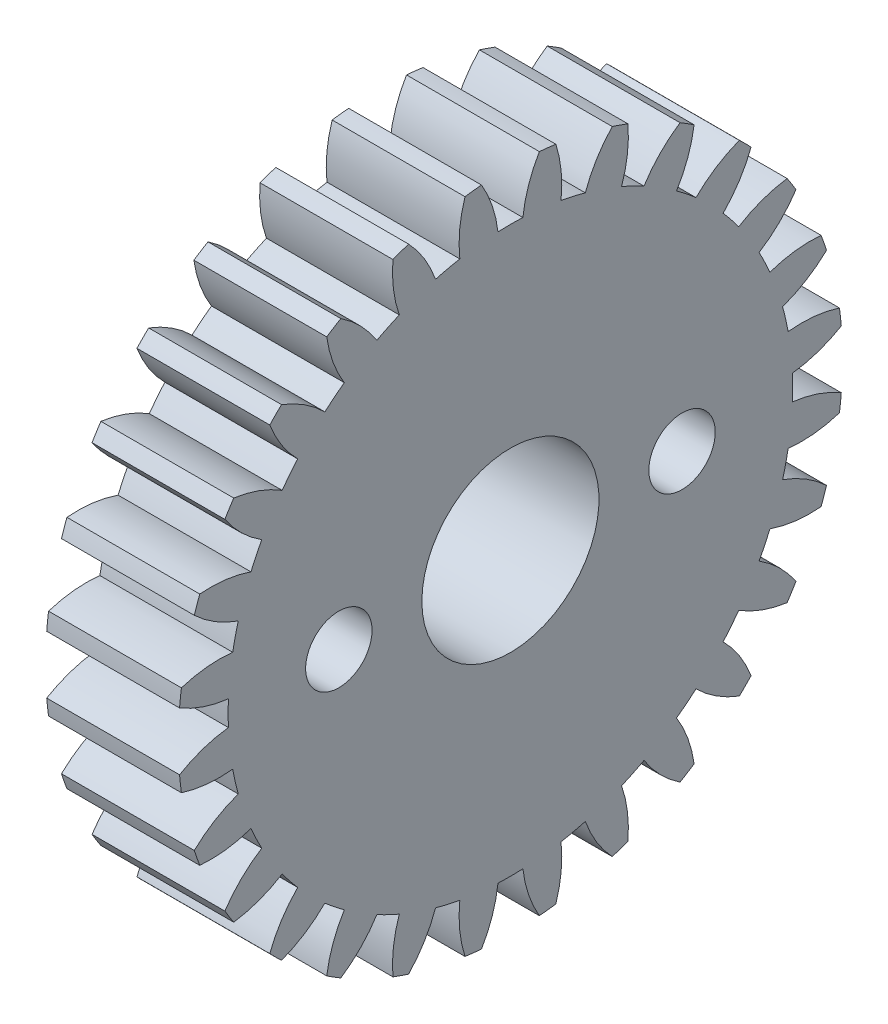
SolidWorks part; units mm, degrees
ref_plane "Plane1" through (0, 0, 0) normal (0, 0, 1) x (1, 0, 0)
ref_plane "Plane2" through (0, 0, 0) normal (0, 1, 0) x (1, 0, 0)
ref_plane "Plane3" through (0, 0, 0) normal (1, 0, 0) x (0, 0, -1)
sketch "HoldingSke" plane through (0, 0, 0) normal (0, 1, 0) x (1, 0, 0)
  line L0 (0, 0) -> (0.8829, -0.4695)
  line L1 (-15, 0) -> (100, 0) construction
  line L2 (0, 0) -> (-2.1039, 2.3779)
  line L3 (0, 0) -> (-11.863, 4.5341)
  line L4 (0, 0) -> (7.6251, 4.0544)
  line L5 (0, 0) -> (-46.8476, -17.4728)
  line L6 (0, 0) -> (-4.9738, -3.3558)
  line L7 (-2.1039, 2.3779) -> (8.6586, 51.2059)
  line L8 (-76.2, 54.61) -> (-74.8, 54.61)
  line L9 (-67.7845, 28.3722) -> (-49.3413, 33.142)
  line L10 (-76.2, 71.12) -> (104.1128, 71.12)
  line L11 (0, 0) -> (-6, 0)
  line L12 (-76.2, 101.6) -> (-76.162, 101.6)
  line L13 (24.9733, 27.94) -> (52.9518, 28.4284)
  line L14 (24.9733, 27.94) -> (24.9743, 27.94)
  line L15 (24.9733, 27.94) -> (100.4006, 29.5858)
  line L16 (-63.627, -1) -> (-12.827, -1)
  circle A0 centre (0, 0) radius 4
  circle A1 centre (0, 0) radius 12.749
  circle A2 centre (0, 0) radius 37.5
  circle A3 centre (0, 0) radius 4
  dimension "MHD" = 25.498
  dimension "Hub_dia" = 75
  dimension "Bore" = 8
  dimension "MBD" = 8
  dimension "Num_teeth" = 28
  dimension "Pitch" = 1
  dimension "Overall_len" = 50
  dimension "Show_teeth" = 28
  dimension "Thickness" = 6
  dimension "OAL" = 50.0001
  dimension "T_dim" = 1.4
  dimension "Ap" = 14.5
  dimension "H" = 19.05
  dimension "Pitch_radius" = 180.3128
  dimension "Width" = 6
  dimension "Backlash" = 0.038
  dimension "Addendum_fac" = 1
  dimension "Dedendum_fac" = 1.25
  dimension "Clearance_fac" = 0.25
  dimension "Dedendum_add" = 0.001
  dimension "Module" = 1
sketch "BasProSke" plane through (0, 0, 0) normal (0, 1, 0) x (1, 0, 0)
  line L0 (-10, 0) -> (60, 0) construction
  line L1 (0, 0) -> (0, 15)
  line L2 (0, 0) -> (6, 0)
  line L3 (6, 0) -> (6, 15)
  line L4 (6, 15) -> (0, 15)
  dimension "Thickness" = 6
  dimension "Diameter" = 30
revolve "Base-Revolve" add sketch "BasProSke" angle 360 about L0
sketch "TooCutSke" plane through (0, 0, 0) normal (1, 0, 0) x (0, 0, -1)
  line L1 (0, 0) -> (0, 107) construction
  line L2 (0, 0) -> (-0.8515, 13.9741) construction
  line L3 (0, 0) -> (-3.1309, 27.7873) construction
  line L4 (-0.8515, 13.9741) -> (-1.5654, 13.8936) construction
  arc A0 (0.5627, 12.7366) -> (-0.5627, 12.7366) centre (0, 0) ccw
  arc A1 (1.3205, 14.9673) -> (-1.3205, 14.9673) centre (0, 0) ccw
  circle A2 centre (0, 0) radius 14 construction
  circle A3 centre (0, 0) radius 13.5541 construction
  arc A4 (-0.5627, 12.7366) -> (-1.3205, 14.9673) centre (-6.1254, 12.091) ccw
  arc A5 (1.3205, 14.9673) -> (0.5627, 12.7366) centre (6.1254, 12.091) ccw
  dimension "Root_dia" = 25.498
  dimension "Overcut_dia" = 30.0508
  dimension "Pitch_dia" = 28
  dimension "Base_dia" = 27.1081
  dimension "Flank_rad" = 5.6
  dimension "Half_ang" = 6.429
  dimension "Half_CT" = 0.7185
extrude "ToothCut" cut sketch "TooCutSke" along normal through all
fillet "Breaks" [suppressed] radius 0.02
fillet "RootFillets" [suppressed] radius 0.251
pattern_circular "TeethCuts" count 28 every 12.857 about axis through (-10, 0, 0) along (1, 0, 0) of "ToothCut", "RootFillets", "Breaks"
sketch "HubNeaOneSke" plane through (0, 0, 0) normal (-1, 0, 0) x (0, 0, 1)
  circle A0 centre (0, 0) radius 12.749
  dimension "Diameter" = 25.498
extrude "HubNearOne" [suppressed] add sketch "HubNeaOneSke" along normal blind 44.0001
sketch "HubNeaBotSke" plane through (0, 0, 0) normal (-1, 0, 0) x (0, 0, 1)
  circle A0 centre (0, 0) radius 12.749
  dimension "Diameter" = 25.498
extrude "HubNearBoth" [suppressed] add sketch "HubNeaBotSke" along normal blind 22
ref_plane "FarPln" through (6, 0, 0) normal (1, 0, 0) x (0, 0, -1)
sketch "HubFarSke" plane through (6, 0, 0) normal (1, 0, 0) x (0, 0, -1)
  circle A0 centre (0, 0) radius 12.749
  dimension "Diameter" = 25.498
extrude "HubFar" [suppressed] add sketch "HubFarSke" along normal blind 22
sketch "BorSke" plane through (0, 0, 0) normal (1, 0, 0) x (0, 0, -1)
  circle A0 centre (0, 0) radius 4
  dimension "Diameter" = 8
extrude "Bore" cut sketch "BorSke" along normal mid plane 100.0001
sketch "KeySke" plane through (0, 0, 0) normal (1, 0, 0) x (0, 0, -1)
  line L0 (-1.5, 0) -> (-1.5, 5.4)
  line L1 (-1.5, 5.4) -> (1.5, 5.4)
  line L2 (1.5, 5.4) -> (1.5, 0)
  line L3 (0, 0) -> (0, 34) construction
  line L4 (-1.5, 0) -> (1.5, 0)
  dimension "Offset" = 5.4
  dimension "Width" = 3
extrude "Keyway" [suppressed] cut sketch "KeySke" along normal mid plane 100.0001
pattern_circular "Keyway2" [suppressed] count 2 every 90 about axis through (-10, 0, 0) along (1, 0, 0)
sketch "Croquis1" plane through (6, 0, 0) normal (1, 0, 0) x (0, 0, -1)
  circle A0 centre (-7.75, 0) radius 1.5
  circle A1 centre (7.75, 0) radius 1.5
  circle A2 centre (0, 0) radius 4 construction
  dimension "D1" = 7.75
  dimension "D2" = 7.75
extrude "Cortar-Extruir1" cut sketch "Croquis1" against normal blind 10
equation "' \"Module@HoldingSke\" = 6.35"
equation "' \"Num_teeth@HoldingSke\" = 12"
equation "' \"Ap@HoldingSke\" =  20"
equation "' \"Ap@HoldingSke\" = 20"
equation "' \"Width@HoldingSke\" = 0.5 * 25.4"
equation "' \"Hub_dia@HoldingSke\"= 1 * 25.4"
equation "' \"Hub_dia@HoldingSke\" = 1 * 25.4"
equation "' \"Overall_len@HoldingSke\" = 1.0 * 25.4"
equation "' \"Bore@HoldingSke\" = 0.75 * 25.4"
equation "' \"T_dim@HoldingSke\" = 0.1 * 25.4"
equation "' \"Width@KeySke\" = 0.25 * 25.4"
equation "' \"Show_teeth@HoldingSke\" = 13"
equation "' \"Backlash@HoldingSke\" = 0.009 * 25.4"
equation "' \"Addendum_fac@HoldingSke\" = 1.0"
equation "' \"Dedendum_fac@HoldingSke\" = 1.25"
equation "' \"Dedendum_add@HoldingSke\" = 0.00005 * 25.4"
equation "' \"Clearance_fac@HoldingSke\" = 0.25"
equation "\"Pitch@HoldingSke\" = 1 / \"Module@HoldingSke\""
equation "\"Overcut_dia@TooCutSke\" = (\"Num_teeth@HoldingSke\" + 2 * \"Addendum_fac@HoldingSke\") / \"Pitch@HoldingSke\" + 0.002 * 25.4"
equation "\"Pitch_dia@TooCutSke\" = \"Num_teeth@HoldingSke\" / \"Pitch@HoldingSke\""
equation "\"Base_dia@TooCutSke\" = \"Num_teeth@HoldingSke\" / \"Pitch@HoldingSke\" * cos((\"Ap@HoldingSke\"  * 3.14159265 / 180))"
equation "\"Root_dia@TooCutSke\" = (\"Num_teeth@HoldingSke\" + 2) / \"Pitch@HoldingSke\" - 2 * (\"Addendum_fac@HoldingSke\" + \"Dedendum_fac@HoldingSke\") / \"Pitch@HoldingSke\" - \"Dedendum_add@HoldingSke\" * 2"
equation "\"Half_ang@TooCutSke\" = 180 / \"Num_teeth@HoldingSke\""
equation "\"Half_CT@TooCutSke\" = \"Num_teeth@HoldingSke\" / \"Pitch@HoldingSke\" * sin((3.14159265 / 2 / \"Num_teeth@HoldingSke\")) / 2 - 7 * \"Backlash@HoldingSke\" / 4"
equation "\"Flank_rad@TooCutSke\" = \"Num_teeth@HoldingSke\" / \"Pitch@HoldingSke\" / 5"
equation "\"Radius@RootFillets\" = \"Clearance_fac@HoldingSke\" / \"Pitch@HoldingSke\" + \"Dedendum_add@HoldingSke\""
equation "\"Break_rad@Breaks\" = 0.02 / \"Pitch@HoldingSke\""
equation "\"Thickness@HoldingSke\" = \"Width@HoldingSke\""
equation "\"OAL@HoldingSke\" = \"Thickness@HoldingSke\""
equation "\"MHD@HoldingSke\" = (\"Num_teeth@HoldingSke\" + 2) / \"Pitch@HoldingSke\" - 2 * (\"Addendum_fac@HoldingSke\" + \"Dedendum_fac@HoldingSke\")  / \"Pitch@HoldingSke\" - \"Dedendum_add@HoldingSke\" * 2"
equation "\"MBD@HoldingSke\" = (\"Num_teeth@HoldingSke\" + 2) / \"Pitch@HoldingSke\" - 2 * (\"Addendum_fac@HoldingSke\" + \"Dedendum_fac@HoldingSke\")  / \"Pitch@HoldingSke\" - \"Dedendum_add@HoldingSke\" * 2 - 0.002 * 25.4"
equation "\"MHD@HoldingSke\" = ((sgn( \"MHD@HoldingSke\" - \"Hub_dia@HoldingSke\" )-1)*( \"MHD@HoldingSke\" - \"Hub_dia@HoldingSke\" ))/-2+ \"Hub_dia@HoldingSke\""
equation "\"MBD@HoldingSke\" = ((sgn( \"MBD@HoldingSke\" - \"Bore@HoldingSke\" )-1)*( \"MBD@HoldingSke\" - \"Bore@HoldingSke\" ))/-2+ \"Bore@HoldingSke\""
equation "\"OAL@HoldingSke\" = ((sgn( \"OAL@HoldingSke\" - \"Overall_len@HoldingSke\" )+1)*( \"OAL@HoldingSke\" - \"Overall_len@HoldingSke\" ))/2 + \"Overall_len@HoldingSke\" + 0.000002 * 25.4"
equation "\"Num_teeth@TeethCuts\" = int( \"Show_teeth@HoldingSke\" ) + 1"
equation "\"Num_teeth@TeethCuts\" = ((sgn( \"Num_teeth@TeethCuts\" - \"Num_teeth@HoldingSke\" )-1)*( \"Num_teeth@TeethCuts\" - \"Num_teeth@HoldingSke\" ))/-2+ \"Num_teeth@HoldingSke\""
equation "\"Num_teeth@TeethCuts\" = ((sgn( \"Num_teeth@TeethCuts\" - 2.0)+1)*( \"Num_teeth@TeethCuts\" - 2.0))/2 +2.0"
equation "\"Angle@TeethCuts\" = 360.0 / \"Num_teeth@HoldingSke\""
equation "\"Diameter@BasProSke\" = (\"Num_teeth@HoldingSke\" + 2 * \"Addendum_fac@HoldingSke\") / \"Pitch@HoldingSke\""
equation "\"Thickness@BasProSke\"  = \"Thickness@HoldingSke\""
equation "' \"Fillet_rad@BasProSke\" =  \"Thickness@HoldingSke\" * 0.05"
equation "' \"Fillet_rad@BasProSke\" = \"Thickness@HoldingSke\" * 0.05"
equation "\"MHD@HoldingSke\" = ((sgn( \"MHD@HoldingSke\" - \"Root_dia@TooCutSke\" )-1)*( \"MHD@HoldingSke\" - \"Root_dia@TooCutSke\" ))/-2+ \"Root_dia@TooCutSke\""
equation "\"Diameter@HubNeaOneSke\" = \"MHD@HoldingSke\""
equation "\"Length@HubNearOne\" = \"OAL@HoldingSke\" - \"Thickness@BasProSke\""
equation "\"Diameter@HubNeaBotSke\" = \"MHD@HoldingSke\""
equation "\"Length@HubNearBoth\" = ( \"OAL@HoldingSke\" - \"Thickness@BasProSke\" ) / 2.0"
equation "\"Thickness@FarPln\" = \"Thickness@BasProSke\""
equation "\"Diameter@HubFarSke\" = \"MHD@HoldingSke\""
equation "\"Length@HubFar\" = ( \"OAL@HoldingSke\" - \"Thickness@BasProSke\" ) / 2.0"
equation "\"Diameter@BorSke\" = \"MBD@HoldingSke\""
equation "\"D1@Bore\" = \"OAL@HoldingSke\" * 2.0"
equation "\"D1@Keyway\" = \"OAL@HoldingSke\" * 2.0"
equation "\"Offset@KeySke\" = \"T_dim@HoldingSke\" + \"MBD@HoldingSke\" / 2.0"
